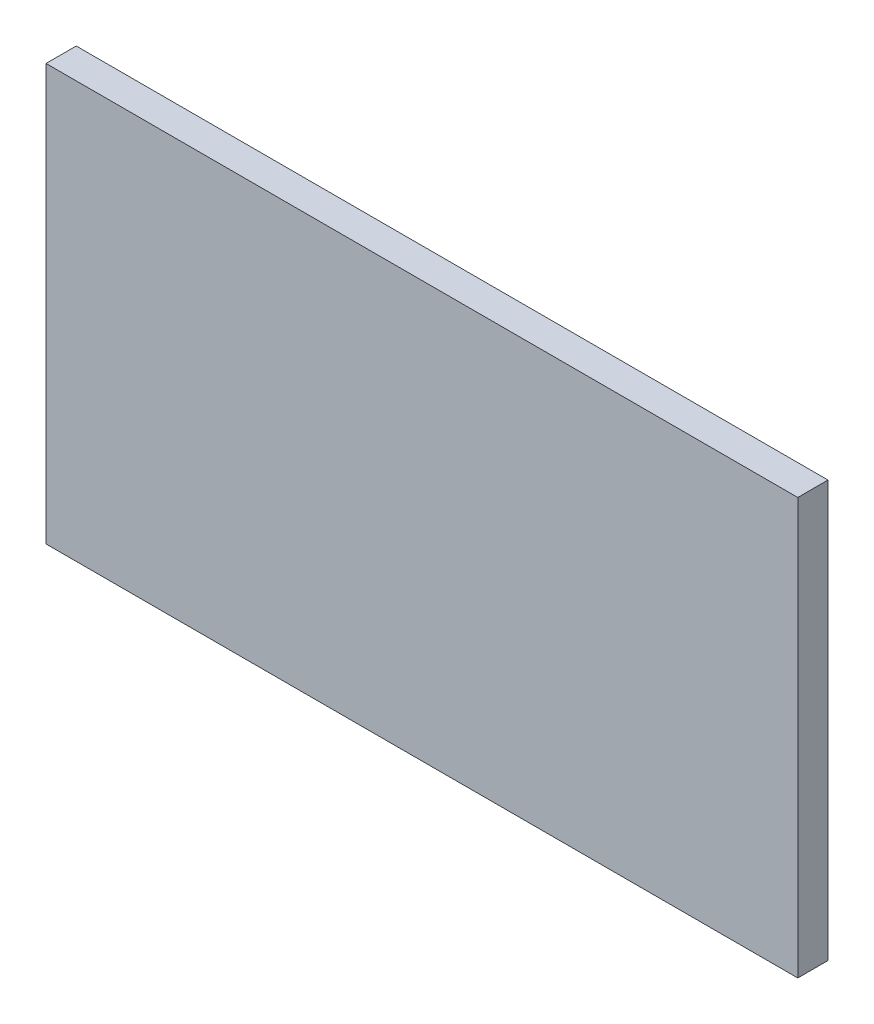
SolidWorks part; units mm, degrees
ref_plane "Front Plane" through (0, 0, 0) normal (0, 0, 1) x (1, 0, 0)
ref_plane "Top Plane" through (0, 0, 0) normal (0, 1, 0) x (1, 0, 0)
ref_plane "Right Plane" through (0, 0, 0) normal (1, 0, 0) x (0, 0, -1)
sketch "Sketch1" plane through (0, 0, 0) normal (0, 0, 1) x (1, 0, 0)
  line L1 (0, 0) -> (448, 0)
  line L2 (0, 0) -> (0, 248)
  line L3 (0, 248) -> (448, 248)
  line L4 (448, 0) -> (448, 248)
  dimension "D1" = 448
  dimension "D2" = 248
extrude "Boss-Extrude1" add sketch "Sketch1" along normal mid plane 18
